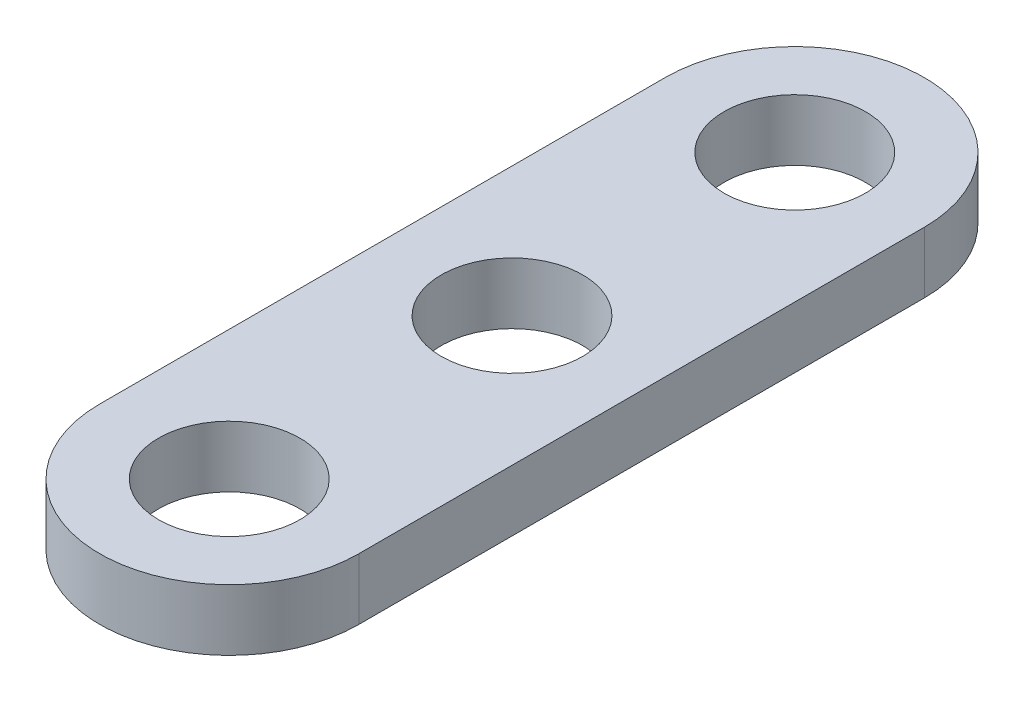
SolidWorks part; units mm, degrees
ref_plane "前视基准面" through (0, 0, 0) normal (0, 0, 1) x (1, 0, 0)
ref_plane "上视基准面" through (0, 0, 0) normal (0, 1, 0) x (1, 0, 0)
ref_plane "右视基准面" through (0, 0, 0) normal (1, 0, 0) x (0, 0, -1)
other "Configuration Table"
sketch "草图1" plane through (0, 0, 0) normal (0, 1, 0) x (1, 0, 0)
  line L0 (-8.564, 0) -> (7.9876, 0) construction
  line L1 (0, 9.8404) -> (0, -10.9109) construction
  line L2 (0, -12) -> (0, 12) construction
  line L3 (-5.5, -12) -> (-5.5, 12)
  line L4 (5.5, -12) -> (5.5, 12)
  circle A0 centre (0, 0) radius 3
  circle A2 centre (0, 12) radius 3
  circle A3 centre (0, -12) radius 3
  arc A4 (-5.5, -12) -> (5.5, -12) centre (0, -12) ccw
  arc A5 (5.5, 12) -> (-5.5, 12) centre (0, 12) ccw
  point P10 (0, 0)
  dimension "D2" = 6
  dimension "D3" = 2
  dimension "D4" = 5.5
  dimension "D7" = 12
  dimension "D6" = 12
  dimension "D1" = 2
extrude "凸台-拉伸1" add sketch "草图1" along normal blind 2.6
